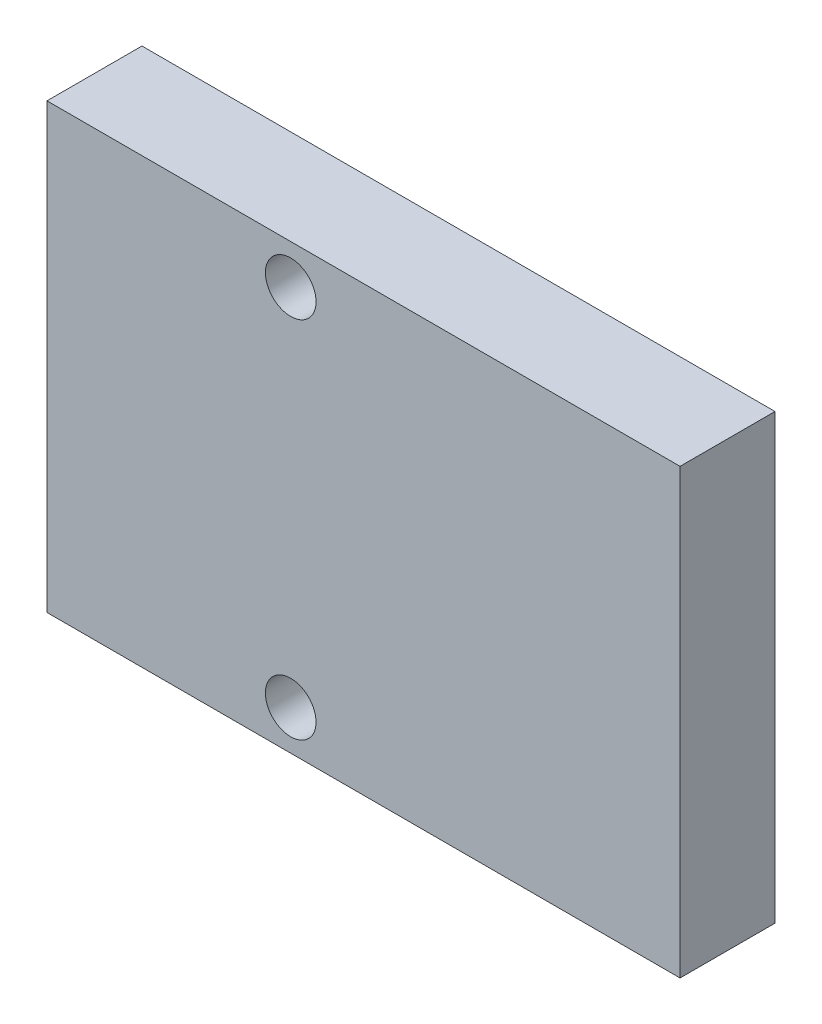
SolidWorks part; units mm, degrees
ref_plane "Plan de face" through (0, 0, 0) normal (0, 0, 1) x (1, 0, 0)
ref_plane "Plan de dessus" through (0, 0, 0) normal (0, 1, 0) x (1, 0, 0)
ref_plane "Plan de droite" through (0, 0, 0) normal (1, 0, 0) x (0, 0, -1)
sketch "Esquisse1" plane through (0, 0, 0) normal (0, 0, 1) x (1, 0, 0)
  line L1 (0, 0) -> (-40, 0)
  line L2 (0, 0) -> (0, 28)
  line L3 (0, 28) -> (-40, 28)
  line L4 (-40, 0) -> (-40, 28)
extrude "Boss.-Extru.1" add sketch "Esquisse1" along normal blind 6
sketch "Esquisse2" plane through (0, 0, 0) normal (0, 0, -1) x (-1, 0, 0)
  line L0 (40, 28) -> (40, 0) construction
  line L1 (0, 28) -> (40, 28) construction
  line L2 (40, 0) -> (0, 0) construction
  circle A0 centre (24.6, 25.5) radius 1.6
  circle A1 centre (24.6, 2.5) radius 1.6
  dimension "D1" = 15.4
  dimension "D3" = 2.5
  dimension "D2" = 2.5
extrude "Enlèv. mat.-Extru.1" cut sketch "Esquisse2" against normal blind 10
